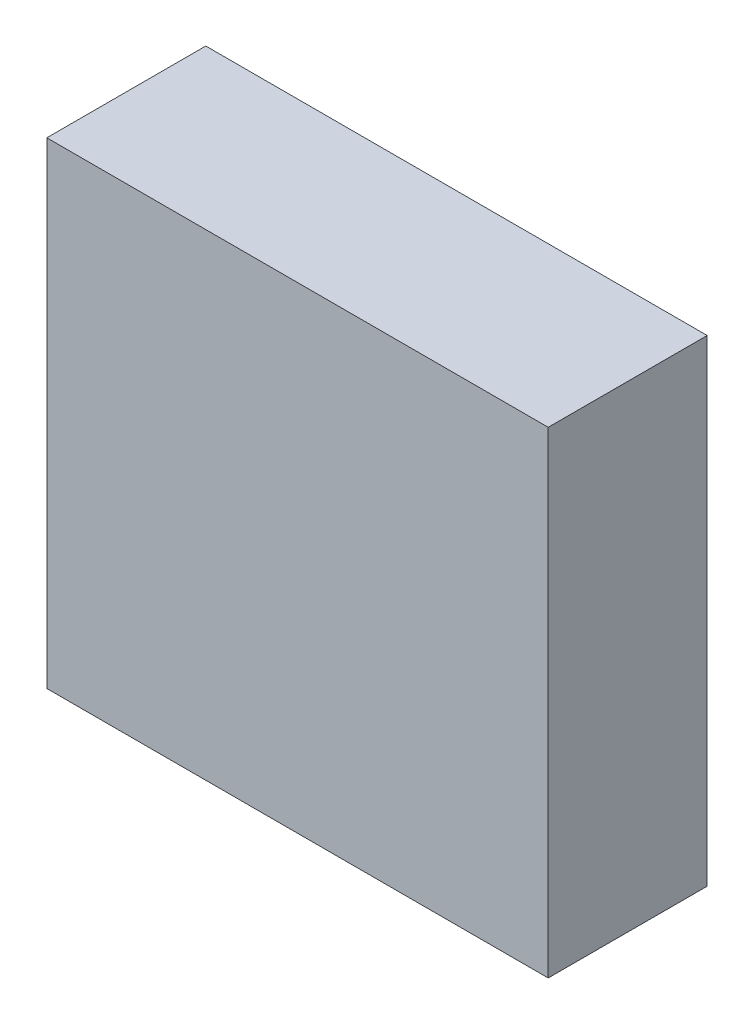
SolidWorks part; units mm, degrees
ref_plane "Front Plane" through (0, 0, 0) normal (0, 0, 1) x (1, 0, 0)
ref_plane "Top Plane" through (0, 0, 0) normal (0, 1, 0) x (1, 0, 0)
ref_plane "Right Plane" through (0, 0, 0) normal (1, 0, 0) x (0, 0, -1)
sketch "Sketch1" plane through (0, 0, 0) normal (0, 1, 0) x (1, 0, 0)
  line L1 (0, 0) -> (40.0558, 0)
  line L2 (0, 0) -> (0, 12.7)
  line L3 (0, 12.7) -> (40.0558, 12.7)
  line L4 (40.0558, 0) -> (40.0558, 12.7)
  dimension "D1" = 40.0558
  dimension "D2" = 12.7
extrude "Boss-Extrude1" add sketch "Sketch1" along normal blind 38.1
